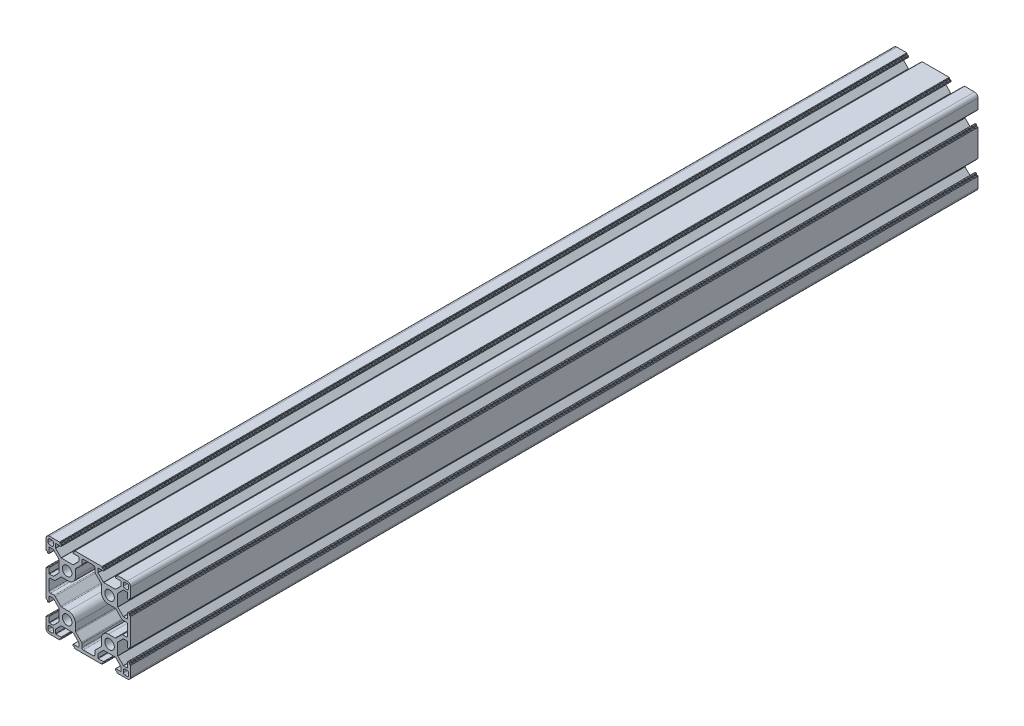
SolidWorks part; units mm, degrees
ref_plane "Front Plane" through (0, 0, 0) normal (0, 0, 1) x (1, 0, 0)
ref_plane "Top Plane" through (0, 0, 0) normal (0, 1, 0) x (1, 0, 0)
ref_plane "Right Plane" through (0, 0, 0) normal (1, 0, 0) x (0, 0, -1)
sketch "Model" plane through (0, 0, 0) normal (0, 0, 1) x (1, 0, 0)
  line L0 (7.05, -27.8) -> (10.6, -27.8)
  line L1 (10.9, -28.1) -> (10.9, -28.7)
  line L2 (10.6, -29) -> (10.1, -29)
  line L3 (9.8, -29.3) -> (9.8, -29.7)
  line L4 (9.5, -30) -> (0, -30)
  line L5 (0, -30) -> (-9.5, -30)
  line L6 (-9.8, -29.7) -> (-9.8, -29.3)
  line L7 (-10.1, -29) -> (-10.6, -29)
  line L8 (-10.9, -28.7) -> (-10.9, -28.1)
  line L9 (-10.6, -27.8) -> (-7.05, -27.8)
  line L10 (-6.75, -27.5) -> (-6.75, -24.9299)
  line L11 (-6.8379, -24.7178) -> (-10.6678, -20.8879)
  line L12 (-10.8799, -20.8) -> (-15, -20.8)
  line L13 (-15, -20.8) -> (-19.1201, -20.8)
  line L14 (-19.3322, -20.8879) -> (-23.1621, -24.7178)
  line L15 (-23.25, -24.9299) -> (-23.25, -27.5)
  line L16 (-22.95, -27.8) -> (-19.4, -27.8)
  line L17 (-19.1, -28.1) -> (-19.1, -28.7)
  line L18 (-19.4, -29) -> (-19.9, -29)
  line L19 (-20.2, -29.3) -> (-20.2, -29.7)
  line L20 (-20.5, -30) -> (-27.5, -30)
  line L21 (-30, -27.5) -> (-30, -20.5)
  line L22 (-29.7, -20.2) -> (-29.3, -20.2)
  line L23 (-29, -19.9) -> (-29, -19.4)
  line L24 (-28.7, -19.1) -> (-28.1, -19.1)
  line L25 (-27.8, -19.4) -> (-27.8, -22.95)
  line L26 (-27.5, -23.25) -> (-24.9299, -23.25)
  line L27 (-24.7178, -23.1621) -> (-20.8879, -19.3322)
  line L28 (-20.8, -19.1201) -> (-20.8, -15)
  line L29 (-20.8, -15) -> (-20.8, -10.8799)
  line L30 (-20.8879, -10.6678) -> (-24.7178, -6.8379)
  line L31 (-24.9299, -6.75) -> (-27.5, -6.75)
  line L32 (-27.8, -7.05) -> (-27.8, -10.6)
  line L33 (-28.1, -10.9) -> (-28.7, -10.9)
  line L34 (-29, -10.6) -> (-29, -10.1)
  line L35 (-29.3, -9.8) -> (-29.7, -9.8)
  line L36 (-30, -9.5) -> (-30, 9.5)
  line L37 (-29.7, 9.8) -> (-29.3, 9.8)
  line L38 (-29, 10.1) -> (-29, 10.6)
  line L39 (-28.7, 10.9) -> (-28.1, 10.9)
  line L40 (-27.8, 10.6) -> (-27.8, 7.05)
  line L41 (-27.5, 6.75) -> (-24.9299, 6.75)
  line L42 (-24.7178, 6.8379) -> (-20.8879, 10.6678)
  line L43 (-20.8, 10.8799) -> (-20.8, 15)
  line L44 (-20.8, 15) -> (-20.8, 19.1201)
  line L45 (-20.8879, 19.3322) -> (-24.7178, 23.1621)
  line L46 (-24.9299, 23.25) -> (-27.5, 23.25)
  line L47 (-27.8, 22.95) -> (-27.8, 19.4)
  line L48 (-28.1, 19.1) -> (-28.7, 19.1)
  line L49 (-29, 19.4) -> (-29, 19.9)
  line L50 (-29.3, 20.2) -> (-29.7, 20.2)
  line L51 (-30, 20.5) -> (-30, 27.5)
  line L52 (-27.5, 30) -> (-20.5, 30)
  line L53 (-20.2, 29.7) -> (-20.2, 29.3)
  line L54 (-19.9, 29) -> (-19.4, 29)
  line L55 (-19.1, 28.7) -> (-19.1, 28.1)
  line L56 (-19.4, 27.8) -> (-22.95, 27.8)
  line L57 (-23.25, 27.5) -> (-23.25, 24.9299)
  line L58 (-23.1621, 24.7178) -> (-19.3322, 20.8879)
  line L59 (-19.1201, 20.8) -> (-15, 20.8)
  line L60 (-15, 20.8) -> (-10.8799, 20.8)
  line L61 (-10.6678, 20.8879) -> (-6.8379, 24.7178)
  line L62 (-6.75, 24.9299) -> (-6.75, 27.5)
  line L63 (-7.05, 27.8) -> (-10.6, 27.8)
  line L64 (-10.9, 28.1) -> (-10.9, 28.7)
  line L65 (-10.6, 29) -> (-10.1, 29)
  line L66 (-9.8, 29.3) -> (-9.8, 29.7)
  line L67 (-9.5, 30) -> (0, 30)
  line L68 (0, 30) -> (9.5, 30)
  line L69 (9.8, 29.7) -> (9.8, 29.3)
  line L70 (10.1, 29) -> (10.6, 29)
  line L71 (10.9, 28.7) -> (10.9, 28.1)
  line L72 (10.6, 27.8) -> (7.05, 27.8)
  line L73 (6.75, 27.5) -> (6.75, 24.9299)
  line L74 (6.8379, 24.7178) -> (10.6678, 20.8879)
  line L75 (10.8799, 20.8) -> (15, 20.8)
  line L76 (15, 20.8) -> (19.1201, 20.8)
  line L77 (19.3322, 20.8879) -> (23.1621, 24.7178)
  line L78 (23.25, 24.9299) -> (23.25, 27.5)
  line L79 (22.95, 27.8) -> (19.4, 27.8)
  line L80 (19.1, 28.1) -> (19.1, 28.7)
  line L81 (19.4, 29) -> (19.9, 29)
  line L82 (20.2, 29.3) -> (20.2, 29.7)
  line L83 (20.5, 30) -> (27.5, 30)
  line L84 (30, 27.5) -> (30, 20.5)
  line L85 (29.7, 20.2) -> (29.3, 20.2)
  line L86 (29, 19.9) -> (29, 19.4)
  line L87 (28.7, 19.1) -> (28.1, 19.1)
  line L88 (27.8, 19.4) -> (27.8, 22.95)
  line L89 (27.5, 23.25) -> (24.9299, 23.25)
  line L90 (24.7178, 23.1621) -> (20.8879, 19.3322)
  line L91 (20.8, 19.1201) -> (20.8, 15)
  line L92 (20.8, 15) -> (20.8, 10.8799)
  line L93 (20.8879, 10.6678) -> (24.7178, 6.8379)
  line L94 (24.9299, 6.75) -> (27.5, 6.75)
  line L95 (27.8, 7.05) -> (27.8, 10.6)
  line L96 (28.1, 10.9) -> (28.7, 10.9)
  line L97 (29, 10.6) -> (29, 10.1)
  line L98 (29.3, 9.8) -> (29.7, 9.8)
  line L99 (30, 9.5) -> (30, -9.5)
  line L100 (29.7, -9.8) -> (29.3, -9.8)
  line L101 (29, -10.1) -> (29, -10.6)
  line L102 (28.7, -10.9) -> (28.1, -10.9)
  line L103 (27.8, -10.6) -> (27.8, -7.05)
  line L104 (27.5, -6.75) -> (24.9299, -6.75)
  line L105 (24.7178, -6.8379) -> (20.8879, -10.6678)
  line L106 (20.8, -10.8799) -> (20.8, -15)
  line L107 (20.8, -15) -> (20.8, -19.1201)
  line L108 (20.8879, -19.3322) -> (24.7178, -23.1621)
  line L109 (24.9299, -23.25) -> (27.5, -23.25)
  line L110 (27.8, -22.95) -> (27.8, -19.4)
  line L111 (28.1, -19.1) -> (28.7, -19.1)
  line L112 (29, -19.4) -> (29, -19.9)
  line L113 (29.3, -20.2) -> (29.7, -20.2)
  line L114 (30, -20.5) -> (30, -27.5)
  line L115 (27.5, -30) -> (20.5, -30)
  line L116 (20.2, -29.7) -> (20.2, -29.3)
  line L117 (19.9, -29) -> (19.4, -29)
  line L118 (19.1, -28.7) -> (19.1, -28.1)
  line L119 (19.4, -27.8) -> (22.95, -27.8)
  line L120 (23.25, -27.5) -> (23.25, -24.9299)
  line L121 (23.1621, -24.7178) -> (19.3322, -20.8879)
  line L122 (19.1201, -20.8) -> (15, -20.8)
  line L123 (15, -20.8) -> (10.8799, -20.8)
  line L124 (10.6678, -20.8879) -> (6.8379, -24.7178)
  line L125 (6.75, -24.9299) -> (6.75, -27.5)
  line L126 (24.75, -25.75) -> (24.75, -27.5)
  line L127 (25.75, -28.5) -> (27.5, -28.5)
  line L128 (28.5, -27.5) -> (28.5, -25.75)
  line L129 (27.5, -24.75) -> (25.75, -24.75)
  line L130 (-27.5, -24.75) -> (-25.75, -24.75)
  line L131 (-24.75, -25.75) -> (-24.75, -27.5)
  line L132 (-25.75, -28.5) -> (-27.5, -28.5)
  line L133 (-28.5, -27.5) -> (-28.5, -25.75)
  line L134 (9.2, -14.2) -> (9.2, -15)
  line L135 (9.2, -15) -> (9.2, -18.8302)
  line L136 (8.9071, -19.5373) -> (4.8429, -23.6015)
  line L137 (4.55, -24.3086) -> (4.55, -26.8)
  line L138 (3.55, -27.8) -> (0, -27.8)
  line L139 (0, -27.8) -> (-3.55, -27.8)
  line L140 (-4.55, -26.8) -> (-4.55, -24.3086)
  line L141 (-4.8429, -23.6015) -> (-8.9071, -19.5373)
  line L142 (-9.2, -18.8302) -> (-9.2, -15)
  line L143 (-9.2, -15) -> (-9.2, -14.2)
  line L144 (-14.2, -9.2) -> (-15, -9.2)
  line L145 (-15, -9.2) -> (-18.8302, -9.2)
  line L146 (-19.5373, -8.9071) -> (-23.6015, -4.8429)
  line L147 (-24.3086, -4.55) -> (-26.8, -4.55)
  line L148 (-27.8, -3.55) -> (-27.8, 0)
  line L149 (-27.8, 0) -> (-27.8, 3.55)
  line L150 (-26.8, 4.55) -> (-24.3086, 4.55)
  line L151 (-23.6015, 4.8429) -> (-19.5373, 8.9071)
  line L152 (-18.8302, 9.2) -> (-15, 9.2)
  line L153 (-15, 9.2) -> (-14.2, 9.2)
  line L154 (-9.2, 14.2) -> (-9.2, 15)
  line L155 (-9.2, 15) -> (-9.2, 18.8302)
  line L156 (-8.9071, 19.5373) -> (-4.8429, 23.6015)
  line L157 (-4.55, 24.3086) -> (-4.55, 26.8)
  line L158 (-3.55, 27.8) -> (0, 27.8)
  line L159 (0, 27.8) -> (3.55, 27.8)
  line L160 (4.55, 26.8) -> (4.55, 24.3086)
  line L161 (4.8429, 23.6015) -> (8.9071, 19.5373)
  line L162 (9.2, 18.8302) -> (9.2, 15)
  line L163 (9.2, 15) -> (9.2, 14.2)
  line L164 (14.2, 9.2) -> (15, 9.2)
  line L165 (15, 9.2) -> (18.8302, 9.2)
  line L166 (19.5373, 8.9071) -> (23.6015, 4.8429)
  line L167 (24.3086, 4.55) -> (26.8, 4.55)
  line L168 (27.8, 3.55) -> (27.8, 0)
  line L169 (27.8, 0) -> (27.8, -3.55)
  line L170 (26.8, -4.55) -> (24.3086, -4.55)
  line L171 (23.6015, -4.8429) -> (19.5373, -8.9071)
  line L172 (18.8302, -9.2) -> (15, -9.2)
  line L173 (15, -9.2) -> (14.2, -9.2)
  line L174 (-15, -19.2587) -> (-15, -19.9121) construction
  line L175 (-27.5, 24.75) -> (-25.75, 24.75)
  line L176 (-24.75, 25.75) -> (-24.75, 27.5)
  line L177 (-25.75, 28.5) -> (-27.5, 28.5)
  line L178 (-28.5, 27.5) -> (-28.5, 25.75)
  line L179 (24.75, 25.75) -> (24.75, 27.5)
  line L180 (25.75, 28.5) -> (27.5, 28.5)
  line L181 (28.5, 27.5) -> (28.5, 25.75)
  line L182 (27.5, 24.75) -> (25.75, 24.75)
  arc A0 (10.9, -28.1) -> (10.6, -27.8) centre (10.6, -28.1) ccw
  arc A1 (10.6, -29) -> (10.9, -28.7) centre (10.6, -28.7) ccw
  arc A2 (10.1, -29) -> (9.8, -29.3) centre (10.1, -29.3) ccw
  arc A3 (9.5, -30) -> (9.8, -29.7) centre (9.5, -29.7) ccw
  arc A4 (-9.8, -29.7) -> (-9.5, -30) centre (-9.5, -29.7) ccw
  arc A5 (-9.8, -29.3) -> (-10.1, -29) centre (-10.1, -29.3) ccw
  arc A6 (-10.9, -28.7) -> (-10.6, -29) centre (-10.6, -28.7) ccw
  arc A7 (-10.6, -27.8) -> (-10.9, -28.1) centre (-10.6, -28.1) ccw
  arc A8 (-7.05, -27.8) -> (-6.75, -27.5) centre (-7.05, -27.5) ccw
  arc A9 (-6.75, -24.9299) -> (-6.8379, -24.7178) centre (-7.05, -24.9299) ccw
  arc A10 (-10.6678, -20.8879) -> (-10.8799, -20.8) centre (-10.8799, -21.1) ccw
  arc A11 (-19.1201, -20.8) -> (-19.3322, -20.8879) centre (-19.1201, -21.1) ccw
  arc A12 (-23.1621, -24.7178) -> (-23.25, -24.9299) centre (-22.95, -24.9299) ccw
  arc A13 (-23.25, -27.5) -> (-22.95, -27.8) centre (-22.95, -27.5) ccw
  arc A14 (-19.1, -28.1) -> (-19.4, -27.8) centre (-19.4, -28.1) ccw
  arc A15 (-19.4, -29) -> (-19.1, -28.7) centre (-19.4, -28.7) ccw
  arc A16 (-19.9, -29) -> (-20.2, -29.3) centre (-19.9, -29.3) ccw
  arc A17 (-20.5, -30) -> (-20.2, -29.7) centre (-20.5, -29.7) ccw
  arc A18 (-30, -27.5) -> (-27.5, -30) centre (-27.5, -27.5) ccw
  arc A19 (-29.7, -20.2) -> (-30, -20.5) centre (-29.7, -20.5) ccw
  arc A20 (-29.3, -20.2) -> (-29, -19.9) centre (-29.3, -19.9) ccw
  arc A21 (-28.7, -19.1) -> (-29, -19.4) centre (-28.7, -19.4) ccw
  arc A22 (-27.8, -19.4) -> (-28.1, -19.1) centre (-28.1, -19.4) ccw
  arc A23 (-27.8, -22.95) -> (-27.5, -23.25) centre (-27.5, -22.95) ccw
  arc A24 (-24.9299, -23.25) -> (-24.7178, -23.1621) centre (-24.9299, -22.95) ccw
  arc A25 (-20.8879, -19.3322) -> (-20.8, -19.1201) centre (-21.1, -19.1201) ccw
  arc A26 (-20.8, -10.8799) -> (-20.8879, -10.6678) centre (-21.1, -10.8799) ccw
  arc A27 (-24.7178, -6.8379) -> (-24.9299, -6.75) centre (-24.9299, -7.05) ccw
  arc A28 (-27.5, -6.75) -> (-27.8, -7.05) centre (-27.5, -7.05) ccw
  arc A29 (-28.1, -10.9) -> (-27.8, -10.6) centre (-28.1, -10.6) ccw
  arc A30 (-29, -10.6) -> (-28.7, -10.9) centre (-28.7, -10.6) ccw
  arc A31 (-29, -10.1) -> (-29.3, -9.8) centre (-29.3, -10.1) ccw
  arc A32 (-30, -9.5) -> (-29.7, -9.8) centre (-29.7, -9.5) ccw
  arc A33 (-29.7, 9.8) -> (-30, 9.5) centre (-29.7, 9.5) ccw
  arc A34 (-29.3, 9.8) -> (-29, 10.1) centre (-29.3, 10.1) ccw
  arc A35 (-28.7, 10.9) -> (-29, 10.6) centre (-28.7, 10.6) ccw
  arc A36 (-27.8, 10.6) -> (-28.1, 10.9) centre (-28.1, 10.6) ccw
  arc A37 (-27.8, 7.05) -> (-27.5, 6.75) centre (-27.5, 7.05) ccw
  arc A38 (-24.9299, 6.75) -> (-24.7178, 6.8379) centre (-24.9299, 7.05) ccw
  arc A39 (-20.8879, 10.6678) -> (-20.8, 10.8799) centre (-21.1, 10.8799) ccw
  arc A40 (-20.8, 19.1201) -> (-20.8879, 19.3322) centre (-21.1, 19.1201) ccw
  arc A41 (-24.7178, 23.1621) -> (-24.9299, 23.25) centre (-24.9299, 22.95) ccw
  arc A42 (-27.5, 23.25) -> (-27.8, 22.95) centre (-27.5, 22.95) ccw
  arc A43 (-28.1, 19.1) -> (-27.8, 19.4) centre (-28.1, 19.4) ccw
  arc A44 (-29, 19.4) -> (-28.7, 19.1) centre (-28.7, 19.4) ccw
  arc A45 (-29, 19.9) -> (-29.3, 20.2) centre (-29.3, 19.9) ccw
  arc A46 (-30, 20.5) -> (-29.7, 20.2) centre (-29.7, 20.5) ccw
  arc A47 (-27.5, 30) -> (-30, 27.5) centre (-27.5, 27.5) ccw
  arc A48 (-20.2, 29.7) -> (-20.5, 30) centre (-20.5, 29.7) ccw
  arc A49 (-20.2, 29.3) -> (-19.9, 29) centre (-19.9, 29.3) ccw
  arc A50 (-19.1, 28.7) -> (-19.4, 29) centre (-19.4, 28.7) ccw
  arc A51 (-19.4, 27.8) -> (-19.1, 28.1) centre (-19.4, 28.1) ccw
  arc A52 (-22.95, 27.8) -> (-23.25, 27.5) centre (-22.95, 27.5) ccw
  arc A53 (-23.25, 24.9299) -> (-23.1621, 24.7178) centre (-22.95, 24.9299) ccw
  arc A54 (-19.3322, 20.8879) -> (-19.1201, 20.8) centre (-19.1201, 21.1) ccw
  arc A55 (-10.8799, 20.8) -> (-10.6678, 20.8879) centre (-10.8799, 21.1) ccw
  arc A56 (-6.8379, 24.7178) -> (-6.75, 24.9299) centre (-7.05, 24.9299) ccw
  arc A57 (-6.75, 27.5) -> (-7.05, 27.8) centre (-7.05, 27.5) ccw
  arc A58 (-10.9, 28.1) -> (-10.6, 27.8) centre (-10.6, 28.1) ccw
  arc A59 (-10.6, 29) -> (-10.9, 28.7) centre (-10.6, 28.7) ccw
  arc A60 (-10.1, 29) -> (-9.8, 29.3) centre (-10.1, 29.3) ccw
  arc A61 (-9.5, 30) -> (-9.8, 29.7) centre (-9.5, 29.7) ccw
  arc A62 (9.8, 29.7) -> (9.5, 30) centre (9.5, 29.7) ccw
  arc A63 (9.8, 29.3) -> (10.1, 29) centre (10.1, 29.3) ccw
  arc A64 (10.9, 28.7) -> (10.6, 29) centre (10.6, 28.7) ccw
  arc A65 (10.6, 27.8) -> (10.9, 28.1) centre (10.6, 28.1) ccw
  arc A66 (7.05, 27.8) -> (6.75, 27.5) centre (7.05, 27.5) ccw
  arc A67 (6.75, 24.9299) -> (6.8379, 24.7178) centre (7.05, 24.9299) ccw
  arc A68 (10.6678, 20.8879) -> (10.8799, 20.8) centre (10.8799, 21.1) ccw
  arc A69 (19.1201, 20.8) -> (19.3322, 20.8879) centre (19.1201, 21.1) ccw
  arc A70 (23.1621, 24.7178) -> (23.25, 24.9299) centre (22.95, 24.9299) ccw
  arc A71 (23.25, 27.5) -> (22.95, 27.8) centre (22.95, 27.5) ccw
  arc A72 (19.1, 28.1) -> (19.4, 27.8) centre (19.4, 28.1) ccw
  arc A73 (19.4, 29) -> (19.1, 28.7) centre (19.4, 28.7) ccw
  arc A74 (19.9, 29) -> (20.2, 29.3) centre (19.9, 29.3) ccw
  arc A75 (20.5, 30) -> (20.2, 29.7) centre (20.5, 29.7) ccw
  arc A76 (30, 27.5) -> (27.5, 30) centre (27.5, 27.5) ccw
  arc A77 (29.7, 20.2) -> (30, 20.5) centre (29.7, 20.5) ccw
  arc A78 (29.3, 20.2) -> (29, 19.9) centre (29.3, 19.9) ccw
  arc A79 (28.7, 19.1) -> (29, 19.4) centre (28.7, 19.4) ccw
  arc A80 (27.8, 19.4) -> (28.1, 19.1) centre (28.1, 19.4) ccw
  arc A81 (27.8, 22.95) -> (27.5, 23.25) centre (27.5, 22.95) ccw
  arc A82 (24.9299, 23.25) -> (24.7178, 23.1621) centre (24.9299, 22.95) ccw
  arc A83 (20.8879, 19.3322) -> (20.8, 19.1201) centre (21.1, 19.1201) ccw
  arc A84 (20.8, 10.8799) -> (20.8879, 10.6678) centre (21.1, 10.8799) ccw
  arc A85 (24.7178, 6.8379) -> (24.9299, 6.75) centre (24.9299, 7.05) ccw
  arc A86 (27.5, 6.75) -> (27.8, 7.05) centre (27.5, 7.05) ccw
  arc A87 (28.1, 10.9) -> (27.8, 10.6) centre (28.1, 10.6) ccw
  arc A88 (29, 10.6) -> (28.7, 10.9) centre (28.7, 10.6) ccw
  arc A89 (29, 10.1) -> (29.3, 9.8) centre (29.3, 10.1) ccw
  arc A90 (30, 9.5) -> (29.7, 9.8) centre (29.7, 9.5) ccw
  arc A91 (29.7, -9.8) -> (30, -9.5) centre (29.7, -9.5) ccw
  arc A92 (29.3, -9.8) -> (29, -10.1) centre (29.3, -10.1) ccw
  arc A93 (28.7, -10.9) -> (29, -10.6) centre (28.7, -10.6) ccw
  arc A94 (27.8, -10.6) -> (28.1, -10.9) centre (28.1, -10.6) ccw
  arc A95 (27.8, -7.05) -> (27.5, -6.75) centre (27.5, -7.05) ccw
  arc A96 (24.9299, -6.75) -> (24.7178, -6.8379) centre (24.9299, -7.05) ccw
  arc A97 (20.8879, -10.6678) -> (20.8, -10.8799) centre (21.1, -10.8799) ccw
  arc A98 (20.8, -19.1201) -> (20.8879, -19.3322) centre (21.1, -19.1201) ccw
  arc A99 (24.7178, -23.1621) -> (24.9299, -23.25) centre (24.9299, -22.95) ccw
  arc A100 (27.5, -23.25) -> (27.8, -22.95) centre (27.5, -22.95) ccw
  arc A101 (28.1, -19.1) -> (27.8, -19.4) centre (28.1, -19.4) ccw
  arc A102 (29, -19.4) -> (28.7, -19.1) centre (28.7, -19.4) ccw
  arc A103 (29, -19.9) -> (29.3, -20.2) centre (29.3, -19.9) ccw
  arc A104 (30, -20.5) -> (29.7, -20.2) centre (29.7, -20.5) ccw
  arc A105 (27.5, -30) -> (30, -27.5) centre (27.5, -27.5) ccw
  arc A106 (20.2, -29.7) -> (20.5, -30) centre (20.5, -29.7) ccw
  arc A107 (20.2, -29.3) -> (19.9, -29) centre (19.9, -29.3) ccw
  arc A108 (19.1, -28.7) -> (19.4, -29) centre (19.4, -28.7) ccw
  arc A109 (19.4, -27.8) -> (19.1, -28.1) centre (19.4, -28.1) ccw
  arc A110 (22.95, -27.8) -> (23.25, -27.5) centre (22.95, -27.5) ccw
  arc A111 (23.25, -24.9299) -> (23.1621, -24.7178) centre (22.95, -24.9299) ccw
  arc A112 (19.3322, -20.8879) -> (19.1201, -20.8) centre (19.1201, -21.1) ccw
  arc A113 (10.8799, -20.8) -> (10.6678, -20.8879) centre (10.8799, -21.1) ccw
  arc A114 (6.8379, -24.7178) -> (6.75, -24.9299) centre (7.05, -24.9299) ccw
  arc A115 (6.75, -27.5) -> (7.05, -27.8) centre (7.05, -27.5) ccw
  arc A116 (25.75, -24.75) -> (24.75, -25.75) centre (25.75, -25.75) ccw
  arc A117 (24.75, -27.5) -> (25.75, -28.5) centre (25.75, -27.5) ccw
  arc A118 (27.5, -28.5) -> (28.5, -27.5) centre (27.5, -27.5) ccw
  arc A119 (28.5, -25.75) -> (27.5, -24.75) centre (27.5, -25.75) ccw
  arc A120 (-24.75, -25.75) -> (-25.75, -24.75) centre (-25.75, -25.75) ccw
  arc A121 (-25.75, -28.5) -> (-24.75, -27.5) centre (-25.75, -27.5) ccw
  arc A122 (-28.5, -27.5) -> (-27.5, -28.5) centre (-27.5, -27.5) ccw
  arc A123 (-27.5, -24.75) -> (-28.5, -25.75) centre (-27.5, -25.75) ccw
  arc A124 (10.6645, -10.6645) -> (9.2, -14.2) centre (14.2, -14.2) ccw
  arc A125 (8.9071, -19.5373) -> (9.2, -18.8302) centre (8.2, -18.8302) ccw
  arc A126 (4.8429, -23.6015) -> (4.55, -24.3086) centre (5.55, -24.3086) ccw
  arc A127 (3.55, -27.8) -> (4.55, -26.8) centre (3.55, -26.8) ccw
  arc A128 (-4.55, -26.8) -> (-3.55, -27.8) centre (-3.55, -26.8) ccw
  arc A129 (-4.55, -24.3086) -> (-4.8429, -23.6015) centre (-5.55, -24.3086) ccw
  arc A130 (-9.2, -18.8302) -> (-8.9071, -19.5373) centre (-8.2, -18.8302) ccw
  arc A131 (-9.2, -14.2) -> (-14.2, -9.2) centre (-14.2, -14.2) ccw
  arc A132 (-19.5373, -8.9071) -> (-18.8302, -9.2) centre (-18.8302, -8.2) ccw
  arc A133 (-23.6015, -4.8429) -> (-24.3086, -4.55) centre (-24.3086, -5.55) ccw
  arc A134 (-27.8, -3.55) -> (-26.8, -4.55) centre (-26.8, -3.55) ccw
  arc A135 (-26.8, 4.55) -> (-27.8, 3.55) centre (-26.8, 3.55) ccw
  arc A136 (-24.3086, 4.55) -> (-23.6015, 4.8429) centre (-24.3086, 5.55) ccw
  arc A137 (-18.8302, 9.2) -> (-19.5373, 8.9071) centre (-18.8302, 8.2) ccw
  arc A138 (-14.2, 9.2) -> (-9.2, 14.2) centre (-14.2, 14.2) ccw
  arc A139 (-8.9071, 19.5373) -> (-9.2, 18.8302) centre (-8.2, 18.8302) ccw
  arc A140 (-4.8429, 23.6015) -> (-4.55, 24.3086) centre (-5.55, 24.3086) ccw
  arc A141 (-3.55, 27.8) -> (-4.55, 26.8) centre (-3.55, 26.8) ccw
  arc A142 (4.55, 26.8) -> (3.55, 27.8) centre (3.55, 26.8) ccw
  arc A143 (4.55, 24.3086) -> (4.8429, 23.6015) centre (5.55, 24.3086) ccw
  arc A144 (9.2, 18.8302) -> (8.9071, 19.5373) centre (8.2, 18.8302) ccw
  arc A145 (9.2, 14.2) -> (14.2, 9.2) centre (14.2, 14.2) ccw
  arc A146 (19.5373, 8.9071) -> (18.8302, 9.2) centre (18.8302, 8.2) ccw
  arc A147 (23.6015, 4.8429) -> (24.3086, 4.55) centre (24.3086, 5.55) ccw
  arc A148 (27.8, 3.55) -> (26.8, 4.55) centre (26.8, 3.55) ccw
  arc A149 (26.8, -4.55) -> (27.8, -3.55) centre (26.8, -3.55) ccw
  arc A150 (24.3086, -4.55) -> (23.6015, -4.8429) centre (24.3086, -5.55) ccw
  arc A151 (18.8302, -9.2) -> (19.5373, -8.9071) centre (18.8302, -8.2) ccw
  arc A152 (14.2, -9.2) -> (10.6645, -10.6645) centre (14.2, -14.2) ccw
  circle A153 centre (15, 15) radius 3.4
  circle A154 centre (15, -15) radius 3.4
  circle A155 centre (-15, -15) radius 3.4
  circle A156 centre (-15, 15) radius 3.4
  arc A157 (-25.75, 24.75) -> (-24.75, 25.75) centre (-25.75, 25.75) ccw
  arc A158 (-24.75, 27.5) -> (-25.75, 28.5) centre (-25.75, 27.5) ccw
  arc A159 (-27.5, 28.5) -> (-28.5, 27.5) centre (-27.5, 27.5) ccw
  arc A160 (-28.5, 25.75) -> (-27.5, 24.75) centre (-27.5, 25.75) ccw
  arc A161 (24.75, 25.75) -> (25.75, 24.75) centre (25.75, 25.75) ccw
  arc A162 (25.75, 28.5) -> (24.75, 27.5) centre (25.75, 27.5) ccw
  arc A163 (28.5, 27.5) -> (27.5, 28.5) centre (27.5, 27.5) ccw
  arc A164 (27.5, 24.75) -> (28.5, 25.75) centre (27.5, 25.75) ccw
  point P509 (0, 0)
extrude "Boss-Extrude1" add sketch "Model" along normal blind 600
